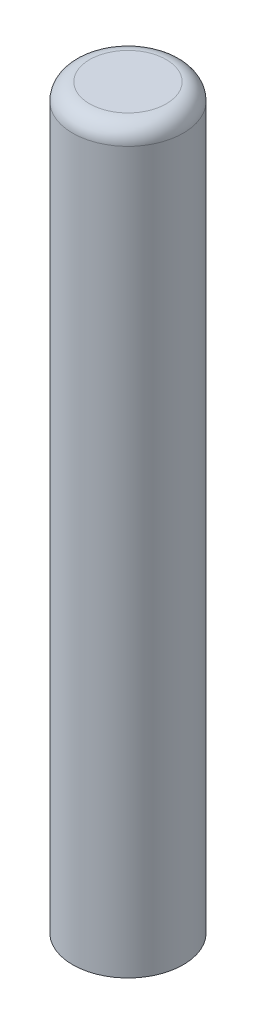
SolidWorks part; units mm, degrees
ref_plane "Front Plane" through (0, 0, 0) normal (0, 0, 1) x (1, 0, 0)
ref_plane "Top Plane" through (0, 0, 0) normal (0, 1, 0) x (1, 0, 0)
ref_plane "Right Plane" through (0, 0, 0) normal (1, 0, 0) x (0, 0, -1)
sketch "Sketch1" plane through (0, 0, 0) normal (0, 1, 0) x (1, 0, 0)
  circle A0 centre (0, 0) radius 7.5
  dimension "D1" = 15
extrude "Main Body" add sketch "Sketch1" along normal blind 100
fillet "Fillet1" radius 2.3 1 edges at (0, 100, 7.5)
